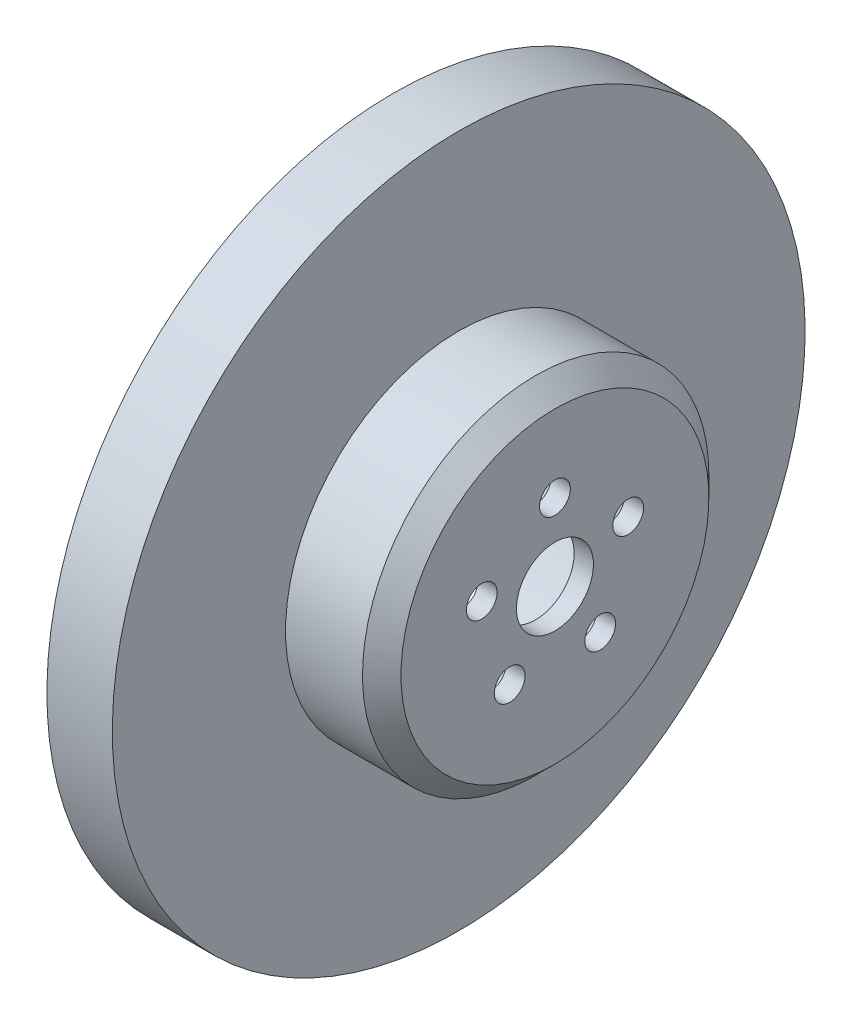
SolidWorks part; units mm, degrees
ref_plane "Piano frontale" through (0, 0, 0) normal (0, 0, 1) x (1, 0, 0)
ref_plane "Piano superiore" through (0, 0, 0) normal (0, 1, 0) x (1, 0, 0)
ref_plane "Piano destro" through (0, 0, 0) normal (1, 0, 0) x (0, 0, -1)
sketch "Schizzo2" plane through (0, 0, 0) normal (0, 0, 1) x (1, 0, 0)
  line L0 (0, 0) -> (0, 70)
  line L1 (0, 70) -> (-50, 70)
  line L2 (-50, 70) -> (-50, 160)
  line L3 (-50, 160) -> (-84, 160)
  line L4 (-84, 160) -> (-84, 60)
  line L5 (-84, 60) -> (-10, 60)
  line L6 (-10, 60) -> (-10, 0)
  line L7 (-10, 0) -> (0, 0)
  line L8 (50, -20) -> (-288.9129, -20) construction
  dimension "D1" = 20
  dimension "D2" = 34
  dimension "D3" = 50
  dimension "D4" = 10
  dimension "D5" = 10
  dimension "D6" = 180
  dimension "D7" = 90
revolve "Rivoluzione1" add sketch "Schizzo2" angle 360 about L8
sketch "Schizzo3" plane through (0, 0, 0) normal (1, 0, 0) x (0, 0, -1)
  circle A0 centre (0, 20) radius 8
  dimension "D1" = 20
extrude "Taglio-Estrusione1" cut sketch "Schizzo3" against normal through all
pattern_circular "RipetizioneCircolare1" count 5 over 360 about axis through (0, -20, 0) along (1, 0, 0) of "Taglio-Estrusione1"
chamfer "Smusso1" distance 10 angle 45 1 edges at (0, 70, 0)
